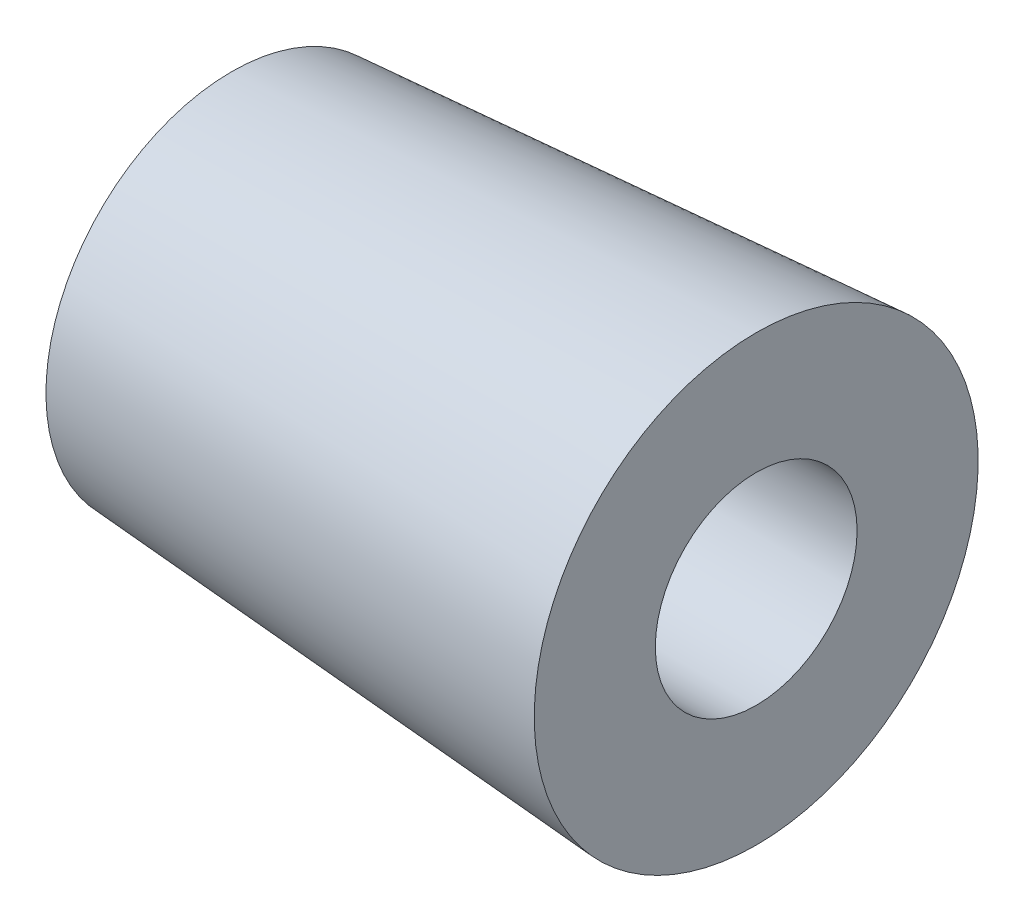
SolidWorks part; units mm, degrees
ref_plane "Front Plane" through (0, 0, 0) normal (0, 0, 1) x (1, 0, 0)
ref_plane "Top Plane" through (0, 0, 0) normal (0, 1, 0) x (1, 0, 0)
ref_plane "Right Plane" through (0, 0, 0) normal (1, 0, 0) x (0, 0, -1)
sketch "Sketch1" plane through (0, 0, 0) normal (0, 0, 1) x (1, 0, 0)
  line L0 (0, 0) -> (7000, 0) construction
  line L1 (4800, 250) -> (4800, 460)
  line L2 (4800, 460) -> (6100, 550)
  line L3 (6100, 550) -> (6100, 250)
  line L4 (6100, 250) -> (4800, 250)
revolve "Revolve1" add sketch "Sketch1" angle 360 about L0
